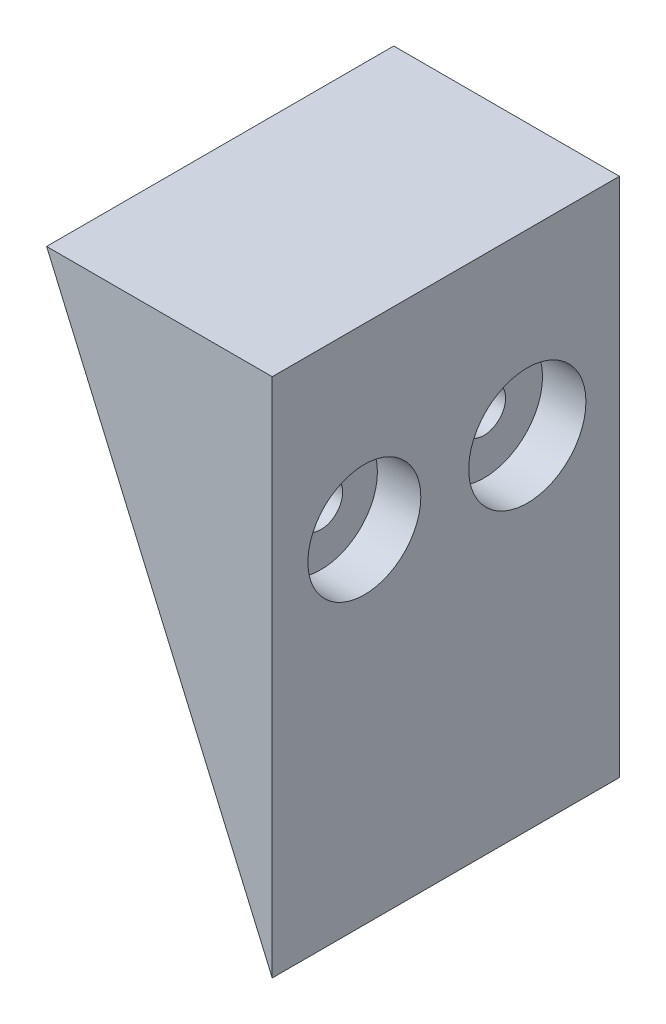
SolidWorks part; units mm, degrees
ref_plane "Front Plane" through (0, 0, 0) normal (0, 0, 1) x (1, 0, 0)
ref_plane "Top Plane" through (0, 0, 0) normal (0, 1, 0) x (1, 0, 0)
ref_plane "Right Plane" through (0, 0, 0) normal (1, 0, 0) x (0, 0, -1)
sketch "Esquisse2" plane through (0, 0, 0) normal (0, 0, 1) x (1, 0, 0)
  line L0 (0, 0) -> (0, 60)
  line L1 (0, 60) -> (-26, 60)
  line L2 (-26, 60) -> (0, 0)
  dimension "D1" = 23.429
  dimension "D2" = 60
extrude "Boss.-Extru.1" add sketch "Esquisse2" along normal blind 40
sketch "Esquisse3" plane through (0, 0, 0) normal (1, 0, 0) x (0, 0, -1)
  line L0 (-37.5, 50) -> (-37.5, 60)
  line L1 (-40, 60) -> (0, 60) construction
  line L2 (-37.5, 60) -> (-2.5, 60)
  line L3 (-2.5, 60) -> (-2.5, 50)
  line L4 (-37.5, 50) -> (-2.5, 50) construction
  line L5 (-20, 50) -> (-20, 60) construction
  arc A0 (-2.5, 50) -> (-37.5, 50) centre (-20, 50) cw
  dimension "D1" = 17.5
  dimension "D2" = 10
sketch "Esquisse4" plane through (0, 0, 0) normal (1, 0, 0) x (0, 0, -1)
  line L0 (-29.388, 39.4403) -> (-10.612, 39.4403) construction
  line L1 (-20, 39.4403) -> (-20, 0) construction
  line L2 (-40, 0) -> (0, 0) construction
  circle A0 centre (-29.388, 39.4403) radius 2.5
  circle A1 centre (-10.612, 39.4403) radius 2.5
  point P4 (-10.612, 39.4403)
extrude "Enlèv. mat.-Extru.2" cut sketch "Esquisse4" against normal blind 80
sketch "Esquisse6" plane through (0, 0, 0) normal (1, 0, 0) x (0, 0, -1)
  circle A0 centre (-29.388, 39.4403) radius 6.5051
  circle A1 centre (-10.612, 39.4403) radius 6.7558
extrude "Enlèv. mat.-Extru.3" cut sketch "Esquisse6" against normal blind 5
